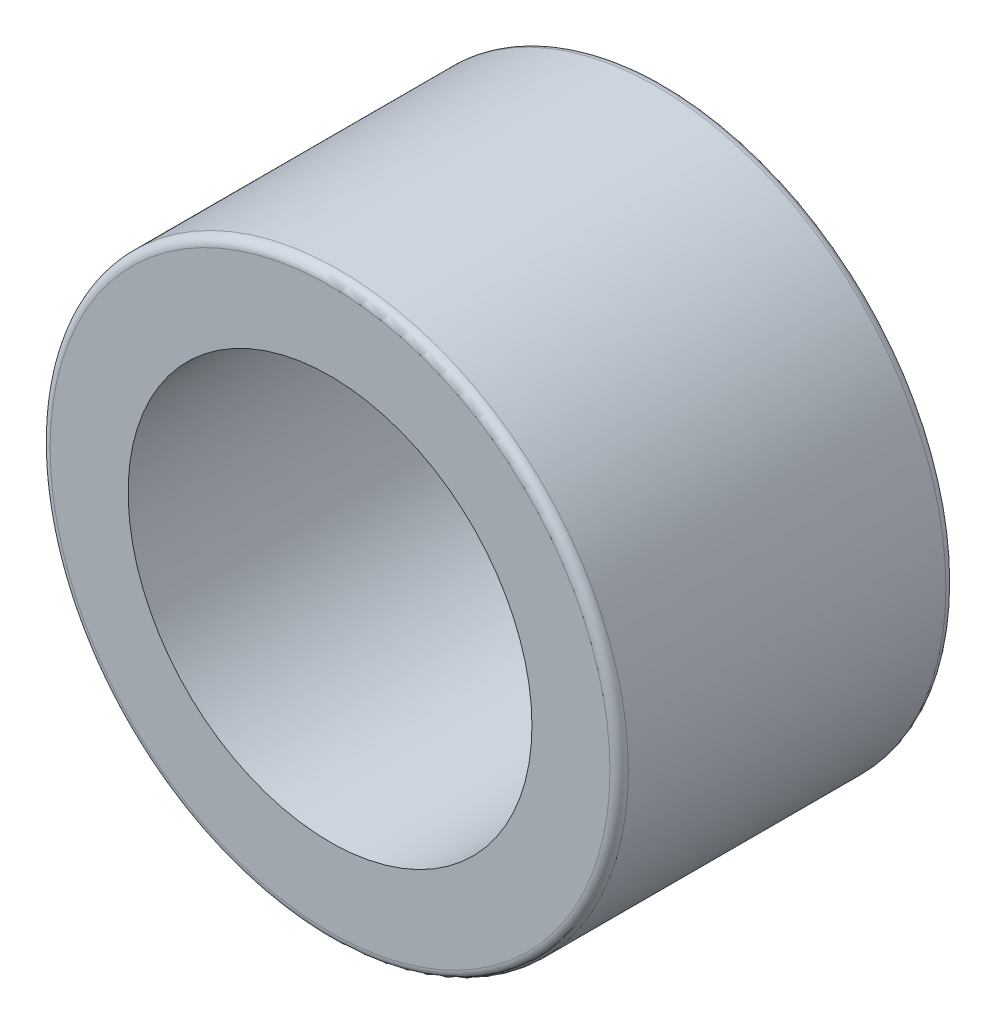
SolidWorks part; units mm, degrees
ref_plane "Front" through (0, 0, 0) normal (0, 0, 1) x (1, 0, 0)
ref_plane "Top" through (0, 0, 0) normal (0, 1, 0) x (1, 0, 0)
ref_plane "Right" through (0, 0, 0) normal (1, 0, 0) x (0, 0, -1)
sketch "Esquisse1" plane through (0, 0, 0) normal (0, 0, 1) x (1, 0, 0)
  circle A0 centre (0, 0) radius 31.5
  circle A1 centre (0, 0) radius 22
  dimension "D1" = 63
  dimension "D2" = 44
extrude "Boss.-Extru.1" add sketch "Esquisse1" along normal blind 36.6
fillet "Congé1" radius 1 2 edges at (31.5, 0, 0) (31.5, 0, 36.6)
